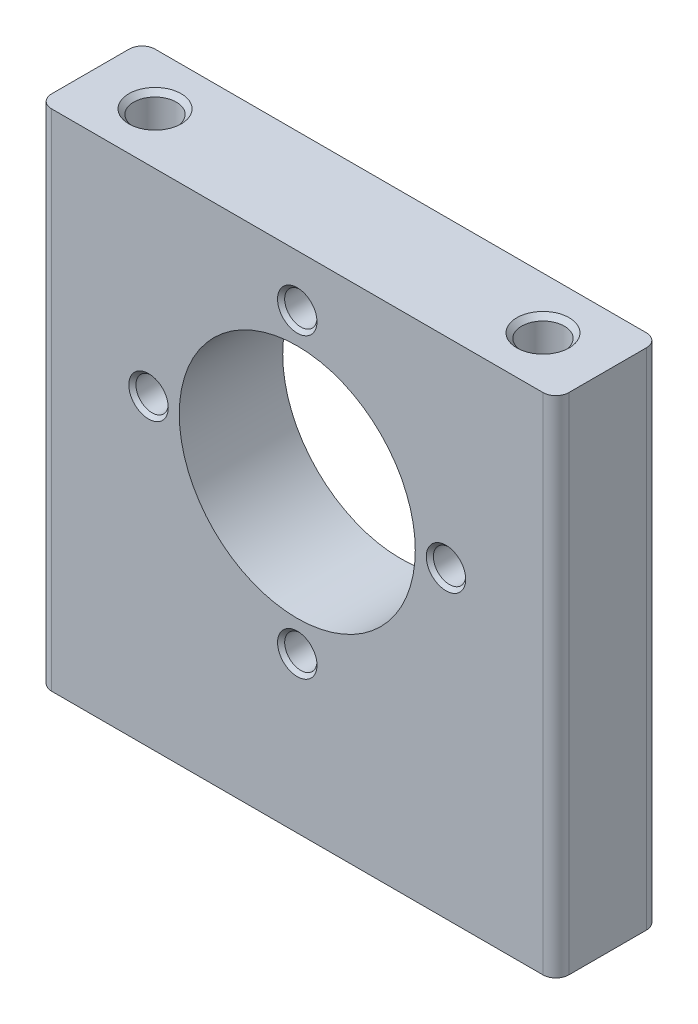
SolidWorks part; units mm, degrees
material "6061 合金"
ref_plane "前视基准面" through (0, 0, 0) normal (0, 0, 1) x (1, 0, 0)
ref_plane "上视基准面" through (0, 0, 0) normal (0, 1, 0) x (1, 0, 0)
ref_plane "右视基准面" through (0, 0, 0) normal (1, 0, 0) x (0, 0, -1)
sketch "草图1" plane through (0, 0, 0) normal (0, 1, 0) x (1, 0, 0)
  line L1 (-20, 4) -> (20, 4)
  line L2 (-20, 4) -> (-20, -4)
  line L3 (-20, -4) -> (20, -4)
  line L4 (20, 4) -> (20, -4)
  line L5 (0, -4) -> (0, 4) construction
  line L6 (-20, 0) -> (20, 0) construction
  point P0 (0, 0)
  dimension "D1" = 8
  dimension "D2" = 40
extrude "凸台-拉伸1" add sketch "草图1" along normal blind 39
sketch "草图2" plane through (0, 39, 0) normal (0, 1, 0) x (1, 0, 0)
  line L0 (-20, 0) -> (20, 0) construction
  line L1 (-20, 4) -> (-20, -4) construction
  line L2 (20, -4) -> (20, 4) construction
  line L3 (0, 4) -> (0, -4) construction
  line L4 (20, 4) -> (-20, 4) construction
  line L5 (-20, -4) -> (20, -4) construction
  point P12 (-15, 0)
  point P13 (15, 0)
  dimension "D1" = 30
hole_wizard "M4 螺纹孔1" positions "草图3" profile "草图4" tap size "M4" standard "GB"
sketch "草图3" plane through (0, 39, 0) normal (0, 1, 0) x (1, 0, 0)
  point P0 (-15, 0)
  point P3 (15, 0)
sketch "草图4" plane through (-15, 39, 0) normal (1, 0, 0) x (0, 0, 1)
  line L0 (0, 0) -> (0, 10.1)
  line L1 (0, 10.1) -> (1.65, 9.1086)
  line L2 (1.65, 9.1086) -> (1.65, 0.375)
  line L3 (1.65, 0.375) -> (2.025, 0)
  line L5 (2.025, 0) -> (0, 0)
  line L6 (-1.65, 0.375) -> (-2.025, 0) construction
  line L10 (0, 10.1) -> (-1.65, 9.1086) construction
  line L11 (0, -6.35) -> (0, 107.95) construction
  dimension "螺纹孔钻头直径" = 3.3
  dimension "螺纹孔钻头深度" = 10.1
  dimension "近端锥形沉头孔直径" = 4.05
  dimension "近端锥形沉头孔角度" = 90
  dimension "导头角度" = 118
cosmetic thread "孔螺蚊线1" parameters "D1"=8, "D2"=4
cosmetic thread "孔螺蚊线2" parameters "D1"=8, "D2"=4
sketch "草图5" plane through (0, 0, 4) normal (0, 0, 1) x (1, 0, 0)
  line L0 (0, 39) -> (0, 0) construction
  line L1 (-20, 39) -> (20, 39) construction
  line L2 (-20, 0) -> (20, 0) construction
  circle A0 centre (0, 23.5) radius 9.125
  dimension "D1" = 18.25
  dimension "D2" = 23.5
extrude "切除-拉伸1" cut sketch "草图5" against normal blind 39
sketch "草图6" plane through (0, 0, 0) normal (0, -1, 0) x (1, 0, 0)
  line L0 (-20, 0) -> (20, 0) construction
  line L1 (0, 4) -> (0, -4) construction
  line L2 (20, -4) -> (-20, -4) construction
  point P9 (-15, 0)
  point P10 (15, 0)
hole_wizard "M4 螺纹孔2" positions "草图7" profile "草图8" tap size "M4" standard "GB"
sketch "草图7" plane through (0, 0, 0) normal (0, -1, 0) x (-1, 0, 0)
  point P0 (15, 0)
  point P3 (-15, 0)
sketch "草图8" plane through (-15, 0, 0) normal (1, 0, 0) x (0, 0, -1)
  line L0 (0, 0) -> (0, 10.1)
  line L1 (0, 10.1) -> (1.65, 9.1086)
  line L2 (1.65, 9.1086) -> (1.65, 0.375)
  line L3 (1.65, 0.375) -> (2.025, 0)
  line L5 (2.025, 0) -> (0, 0)
  line L6 (-1.65, 0.375) -> (-2.025, 0) construction
  line L10 (0, 10.1) -> (-1.65, 9.1086) construction
  line L11 (0, -6.35) -> (0, 107.95) construction
  dimension "螺纹孔钻头直径" = 3.3
  dimension "螺纹孔钻头深度" = 10.1
  dimension "近端锥形沉头孔直径" = 4.05
  dimension "近端锥形沉头孔角度" = 90
  dimension "导头角度" = 118
cosmetic thread "孔螺蚊线3" parameters "D1"=8, "D2"=4
cosmetic thread "孔螺蚊线4" parameters "D1"=8, "D2"=4
sketch "草图9" plane through (0, 0, 4) normal (0, 0, 1) x (1, 0, 0)
  line L0 (0, 39) -> (0, 0) construction
  line L1 (-20, 39) -> (20, 39) construction
  line L2 (-20, 23.5) -> (20, 23.5) construction
  line L3 (-20, 39) -> (-20, 0) construction
  line L4 (20, 39) -> (20, 0) construction
  point P12 (0, 35)
  point P13 (0, 23.5)
  point P17 (11.5, 23.5)
  point P18 (0, 12)
  point P19 (-11.5, 23.5)
  dimension "D1" = 11.5
  dimension "D2" = 4
hole_wizard "M3 螺纹孔1" positions "草图10" profile "草图11" tap size "M3" standard "GB" end condition through all
sketch "草图10" plane through (0, 0, 4) normal (0, 0, 1) x (1, 0, 0)
  point P0 (0, 35)
  point P3 (-11.5, 23.5)
  point P6 (11.5, 23.5)
  point P9 (0, 12)
sketch "草图11" plane through (0, 35, 4) normal (1, 0, 0) x (0, -1, 0)
  line L0 (0, 0) -> (0, 8)
  line L1 (0, 8) -> (1.25, 8)
  line L2 (1.25, 8) -> (1.25, 0.275)
  line L3 (1.25, 0.275) -> (1.525, 0)
  line L5 (1.525, 0) -> (0, 0)
  line L6 (-1.25, 0.275) -> (-1.525, 0) construction
  line L11 (0, -6.35) -> (0, 107.95) construction
  dimension "通孔螺纹孔钻头直径" = 2.5
  dimension "通孔螺纹孔钻头深度" = 8
  dimension "近端锥形沉头孔直径" = 3.05
  dimension "近端锥形沉头孔角度" = 90
cosmetic thread "孔螺蚊线5" parameters "D2"=3
cosmetic thread "孔螺蚊线6" parameters "D2"=3
cosmetic thread "孔螺蚊线7" parameters "D2"=3
cosmetic thread "孔螺蚊线8" parameters "D2"=3
fillet "圆角1" radius 1 4 edges at (20, 19.5, -4) (20, 19.5, 4) (-20, 19.5, -4) (-20, 19.5, 4)
